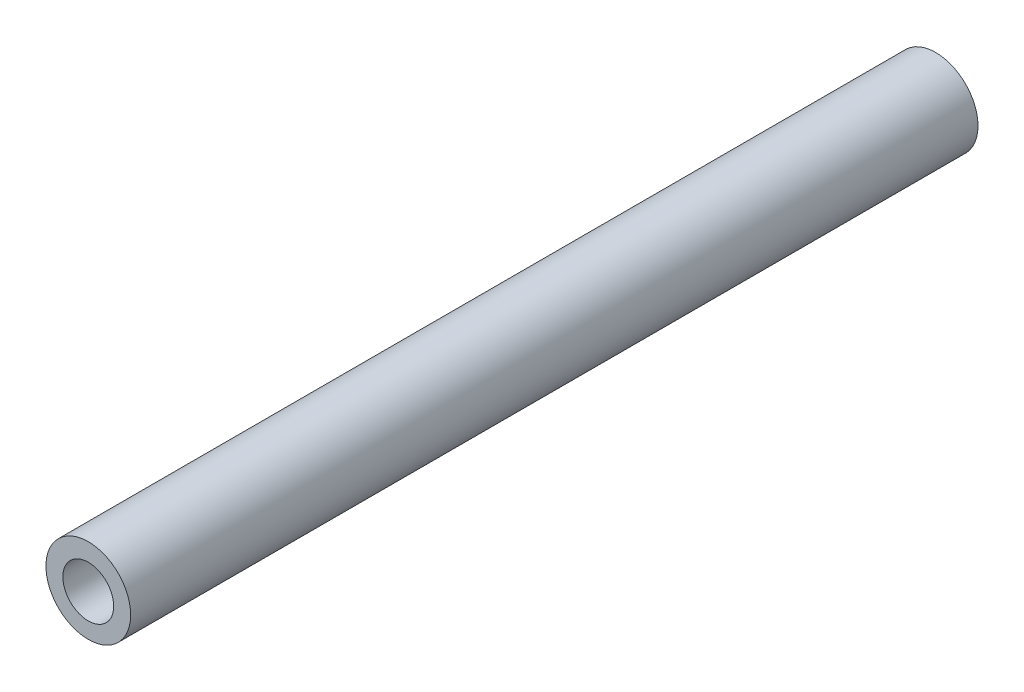
SolidWorks part; units mm, degrees
ref_plane "Front Plane" through (0, 0, 0) normal (0, 0, 1) x (1, 0, 0)
ref_plane "Top Plane" through (0, 0, 0) normal (0, 1, 0) x (1, 0, 0)
ref_plane "Right Plane" through (0, 0, 0) normal (1, 0, 0) x (0, 0, -1)
sketch "Sketch1" plane through (0, 0, 0) normal (0, 0, 1) x (1, 0, 0)
  circle A0 centre (0.0523, 0.0784) radius 3
  circle A1 centre (0.0523, 0.183) radius 5
  dimension "D1" = 6
  dimension "D2" = 10
extrude "Boss-Extrude1" add sketch "Sketch1" along normal blind 100
